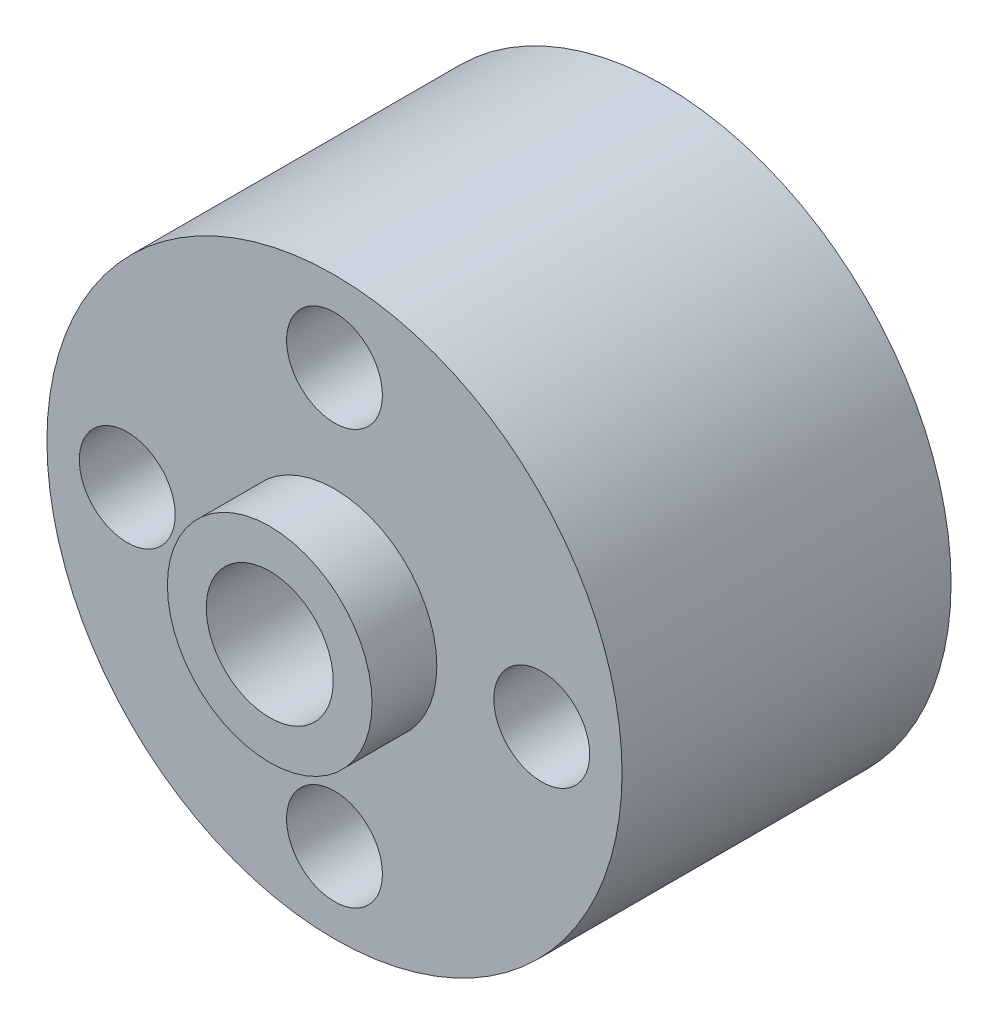
SolidWorks part; units mm, degrees
material "6061 Alloy"
ref_plane "Front Plane" through (0, 0, 0) normal (0, 0, 1) x (1, 0, 0)
ref_plane "Top Plane" through (0, 0, 0) normal (0, 1, 0) x (1, 0, 0)
ref_plane "Right Plane" through (0, 0, 0) normal (1, 0, 0) x (0, 0, -1)
sketch "Sketch1" plane through (0, 0, 0) normal (0, 0, 1) x (1, 0, 0)
  circle A0 centre (0, 0) radius 11.1
  dimension "D1" = 22.2
extrude "Extrude1" add sketch "Sketch1" against normal blind 12.7
sketch "Sketch3" plane through (0, 0, 0) normal (0, 0, 1) x (1, 0, 0)
  circle A1 centre (8, 0) radius 1.85
  circle A2 centre (-8, 0) radius 1.85
  circle A3 centre (0, -8) radius 1.85
  circle A4 centre (0, 8) radius 1.85
extrude "Cut-Extrude1" cut sketch "Sketch3" against normal through all
sketch "Sketch6" plane through (0, 0, 0) normal (0, 0, 1) x (1, 0, 0)
  circle A0 centre (0, 0) radius 3.95
  dimension "D1" = 7.9
extrude "Extrude3" add sketch "Sketch6" along normal blind 2.5
sketch "Sketch7" plane through (0, 0, -12.7) normal (0, 0, -1) x (-1, 0, 0)
  circle A0 centre (0, 0) radius 3.95
  dimension "D1" = 7.9
extrude "Extrude4" add sketch "Sketch7" along normal blind 2.5
sketch "Sketch8" plane through (0, 0, 2.5) normal (0, 0, 1) x (1, 0, 0)
  circle A0 centre (0, 0) radius 2.45
  dimension "D1" = 4.9
extrude "Cut-Extrude2" cut sketch "Sketch8" against normal through all
